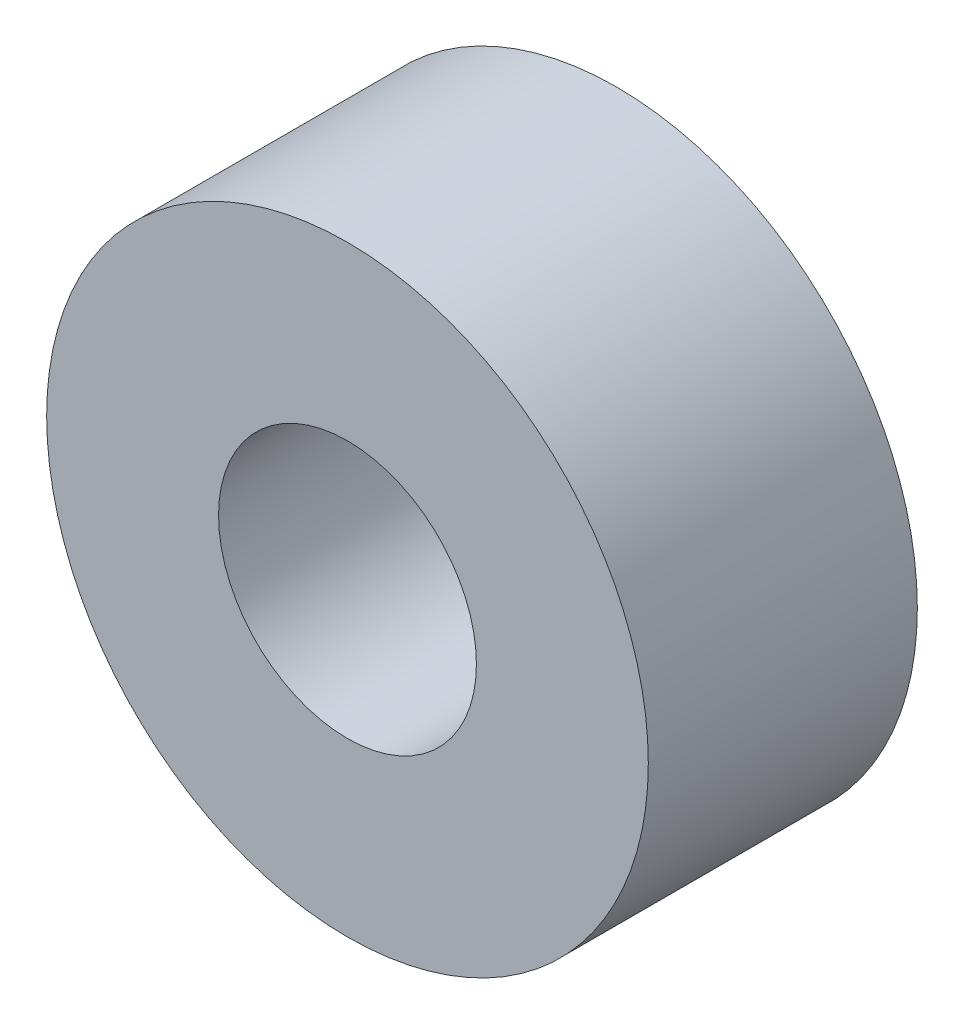
SolidWorks part; units mm, degrees
ref_plane "Front Plane" through (0, 0, 0) normal (0, 0, 1) x (1, 0, 0)
ref_plane "Top Plane" through (0, 0, 0) normal (0, 1, 0) x (1, 0, 0)
ref_plane "Right Plane" through (0, 0, 0) normal (1, 0, 0) x (0, 0, -1)
sketch "Sketch1" plane through (0, 0, 0) normal (0, 0, 1) x (1, 0, 0)
  circle A0 centre (0, 0) radius 3.81
  circle A1 centre (0, 0) radius 8.89
  dimension "D1" = 17.78
  dimension "D2" = 7.62
extrude "Boss-Extrude1" add sketch "Sketch1" along normal blind 7.9502
